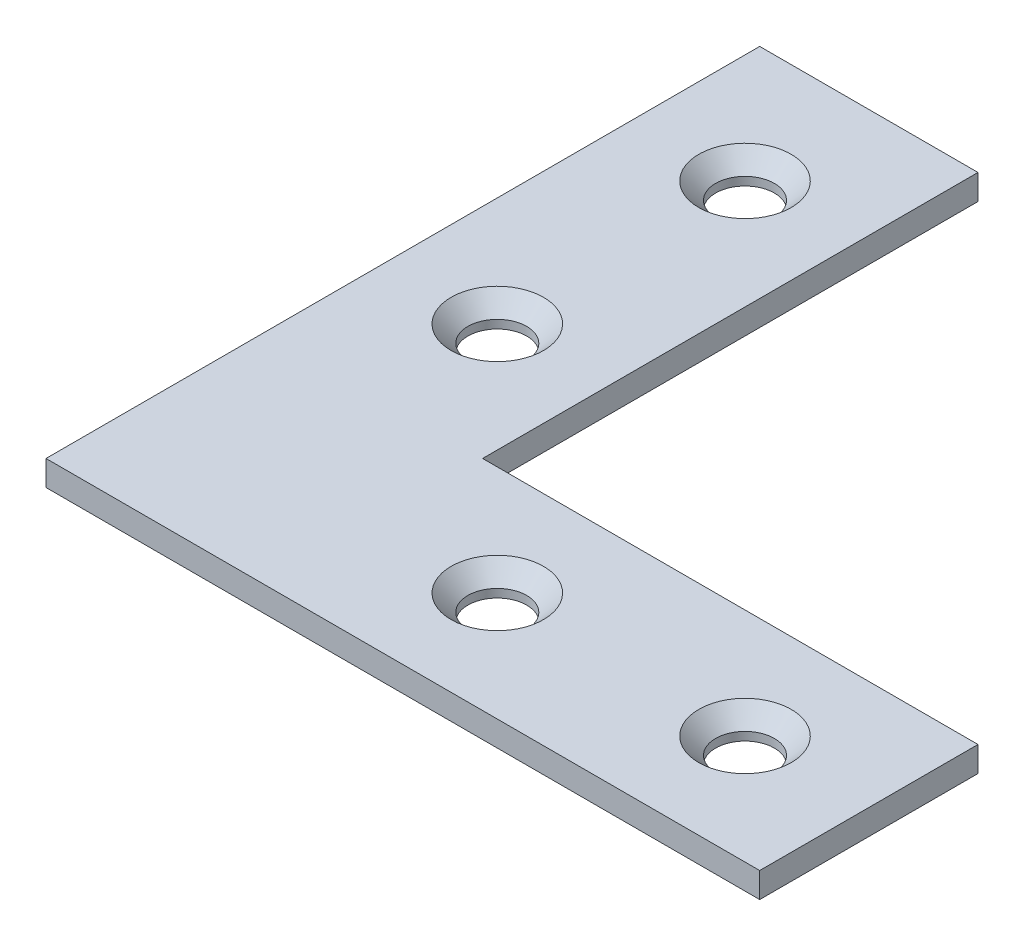
SolidWorks part; units mm, degrees
ref_plane "Front Plane" through (0, 0, 0) normal (0, 0, 1) x (1, 0, 0)
ref_plane "Top Plane" through (0, 0, 0) normal (0, 1, 0) x (1, 0, 0)
ref_plane "Right Plane" through (0, 0, 0) normal (1, 0, 0) x (0, 0, -1)
sketch "Sketch1" plane through (0, 0, 0) normal (0, 1, 0) x (1, 0, 0)
  line L0 (0, 0) -> (29.5, 0)
  line L1 (29.5, 0) -> (29.5, -13)
  line L2 (29.5, -13) -> (-13, -13)
  line L3 (-13, -13) -> (-13, 29.5)
  line L4 (-13, 29.5) -> (0, 29.5)
  line L5 (0, 29.5) -> (0, 0)
  line L8 (-6.5, 14.75) -> (-6.5, 0) construction
  line L9 (0, 14.75) -> (-13, 14.75) construction
  line L10 (0, -6.5) -> (14.75, -6.5) construction
  line L11 (14.75, -6.5) -> (14.75, -13) construction
  circle A0 centre (-6.5, 7.375) radius 1.75
  circle A1 centre (7.375, -6.5) radius 1.75
  circle A2 centre (-6.5, 22.125) radius 1.75
  circle A3 centre (22.125, -6.5) radius 1.75
  dimension "D1" = 13
  dimension "D2" = 13
  dimension "D3" = 42.5
  dimension "D4" = 42.5
extrude "Boss-Extrude1" add sketch "Sketch1" along normal blind 1.5
chamfer "Chamfer1" distance 1 angle 45 4 edges at (22.125, 1.5, 4.75) (7.375, 1.5, 8.25) (-6.5, 1.5, -5.625) (-6.5, 1.5, -23.875)
